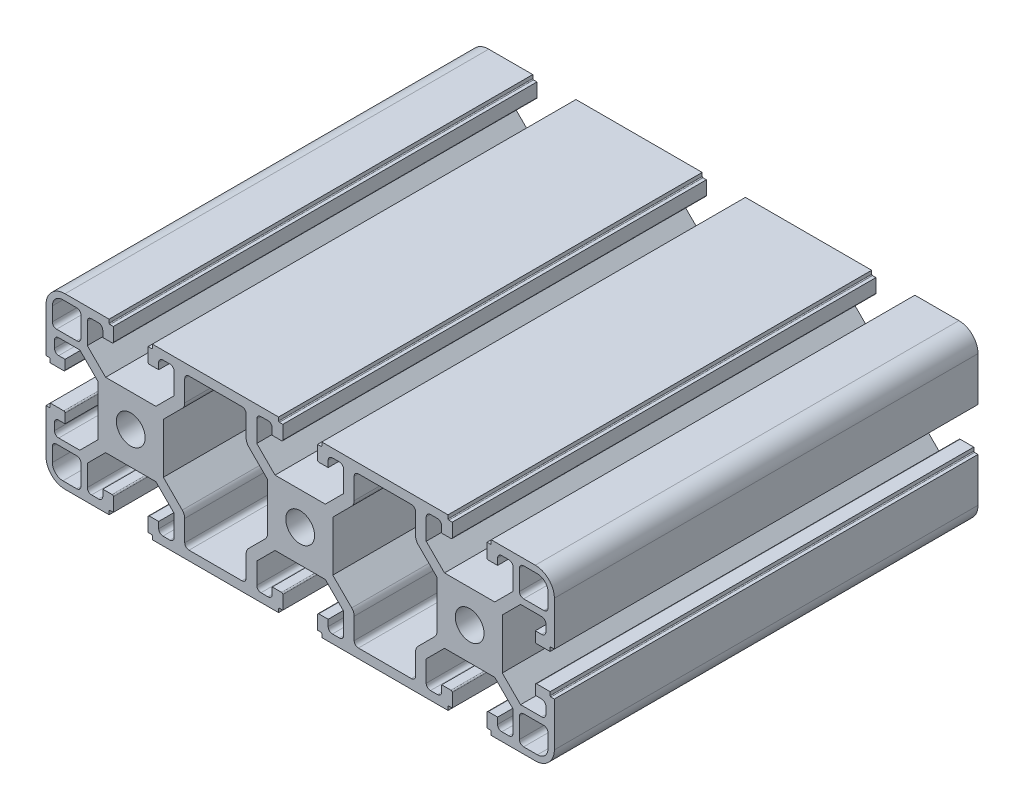
SolidWorks part; units mm, degrees
ref_plane "前视基准面" through (0, 0, 0) normal (0, 0, 1) x (1, 0, 0)
ref_plane "上视基准面" through (0, 0, 0) normal (0, 1, 0) x (1, 0, 0)
ref_plane "右视基准面" through (0, 0, 0) normal (1, 0, 0) x (0, 0, -1)
sketch "草图1" plane through (0, 0, 0) normal (0, 0, 1) x (1, 0, 0)
  line L0 (-45.8856, 20.757) -> (-56.2856, 20.757)
  line L1 (-60.7856, 16.257) -> (-60.7856, 5.857)
  line L2 (-47.3856, 16.257) -> (-47.3856, 17.757)
  line L3 (-48.3856, 18.757) -> (-50.0356, 18.757)
  line L4 (-51.0356, 17.757) -> (-51.0356, 12.7748)
  line L5 (-44.8856, 19.757) -> (-45.6856, 19.757)
  line L6 (-45.8856, 19.957) -> (-45.8856, 20.757)
  line L7 (-60.7856, 5.857) -> (-59.9856, 5.857)
  line L8 (-59.7856, 5.657) -> (-59.7856, 4.857)
  line L9 (-56.2856, 7.357) -> (-56.2856, 5.157)
  line L10 (-56.5856, 4.857) -> (-59.7856, 4.857)
  line L11 (-44.8856, 19.757) -> (-44.8856, 16.557)
  line L12 (-45.1856, 16.257) -> (-47.3856, 16.257)
  line L13 (-46.7178, 8.457) -> (-34.8534, 8.457)
  line L14 (-59.2896, 16.761) -> (-59.2896, 13.507)
  line L15 (-58.2896, 12.507) -> (-53.5356, 12.507)
  line L16 (-52.5356, 13.507) -> (-52.5356, 18.261)
  line L17 (-53.5356, 19.261) -> (-56.7896, 19.261)
  line L18 (-46.7178, -6.943) -> (-34.8534, -6.943)
  line L19 (-48.4856, 6.6892) -> (-48.4856, -5.1752)
  line L21 (-33.0856, -5.1752) -> (-33.0856, 6.6892)
  line L23 (-52.8034, 11.007) -> (-48.4856, 6.6892)
  line L24 (-51.0356, 12.7748) -> (-46.7178, 8.457)
  line L25 (-56.2856, 7.357) -> (-57.7856, 7.357)
  line L26 (-58.7856, 8.357) -> (-58.7856, 10.007)
  line L27 (-57.7856, 11.007) -> (-52.8034, 11.007)
  line L28 (-35.6856, 20.757) -> (-25.2856, 20.757)
  line L29 (-34.1856, 16.257) -> (-34.1856, 17.757)
  line L30 (-33.1856, 18.757) -> (-31.5356, 18.757)
  line L31 (-30.5356, 17.757) -> (-30.5356, 12.7748)
  line L32 (-28.0356, 17.557) -> (-28.0356, 12.5677)
  line L33 (-36.6856, 19.757) -> (-35.8856, 19.757)
  line L34 (-35.6856, 19.957) -> (-35.6856, 20.757)
  line L35 (-36.6856, 19.757) -> (-36.6856, 16.557)
  line L36 (-36.3856, 16.257) -> (-34.1856, 16.257)
  line L37 (-28.6214, 11.1535) -> (-33.0856, 6.6892)
  line L38 (-30.5356, 12.7748) -> (-34.8534, 8.457)
  line L39 (-45.8856, -19.243) -> (-56.2856, -19.243)
  line L40 (-60.7856, -14.743) -> (-60.7856, -4.343)
  line L41 (-47.3856, -14.743) -> (-47.3856, -16.243)
  line L42 (-48.3856, -17.243) -> (-50.0356, -17.243)
  line L43 (-51.0356, -16.243) -> (-51.0356, -11.2608)
  line L44 (-44.8856, -18.243) -> (-45.6856, -18.243)
  line L45 (-45.8856, -18.443) -> (-45.8856, -19.243)
  line L46 (-60.7856, -4.343) -> (-59.9856, -4.343)
  line L47 (-59.7856, -4.143) -> (-59.7856, -3.343)
  line L48 (-56.2856, -5.843) -> (-56.2856, -3.643)
  line L49 (-56.5856, -3.343) -> (-59.7856, -3.343)
  line L50 (-44.8856, -18.243) -> (-44.8856, -15.043)
  line L51 (-45.1856, -14.743) -> (-47.3856, -14.743)
  line L52 (-59.2896, -15.247) -> (-59.2896, -11.993)
  line L53 (-58.2896, -10.993) -> (-53.5356, -10.993)
  line L54 (-52.5356, -11.993) -> (-52.5356, -16.747)
  line L55 (-53.5356, -17.747) -> (-56.7896, -17.747)
  line L56 (-52.8034, -9.493) -> (-48.4856, -5.1752)
  line L57 (-51.0356, -11.2608) -> (-46.7178, -6.943)
  line L58 (-56.2856, -5.843) -> (-57.7856, -5.843)
  line L59 (-58.7856, -6.843) -> (-58.7856, -8.493)
  line L60 (-57.7856, -9.493) -> (-52.8034, -9.493)
  line L61 (-35.6856, -19.243) -> (-25.2856, -19.243)
  line L62 (-34.1856, -14.743) -> (-34.1856, -16.243)
  line L63 (-33.1856, -17.243) -> (-31.5356, -17.243)
  line L64 (-30.5356, -16.243) -> (-30.5356, -11.2608)
  line L65 (-36.6856, -18.243) -> (-35.8856, -18.243)
  line L66 (-35.6856, -18.443) -> (-35.6856, -19.243)
  line L67 (-36.6856, -18.243) -> (-36.6856, -15.043)
  line L68 (-36.3856, -14.743) -> (-34.1856, -14.743)
  line L69 (-28.6214, -9.6394) -> (-33.0856, -5.1752)
  line L70 (-30.5356, -11.2608) -> (-34.8534, -6.943)
  line L71 (-5.8856, 20.757) -> (-16.2856, 20.757)
  line L72 (-7.3856, 16.257) -> (-7.3856, 17.757)
  line L73 (-8.3856, 18.757) -> (-10.0356, 18.757)
  line L74 (-11.0356, 17.757) -> (-11.0356, 12.7748)
  line L75 (-13.5356, 17.557) -> (-13.5356, 12.5677)
  line L76 (-4.8856, 19.757) -> (-5.6856, 19.757)
  line L77 (-5.8856, 19.957) -> (-5.8856, 20.757)
  line L78 (-4.8856, 19.757) -> (-4.8856, 16.557)
  line L79 (-5.1856, 16.257) -> (-7.3856, 16.257)
  line L80 (-6.7178, 8.457) -> (5.1466, 8.457)
  line L81 (-6.7178, -6.943) -> (5.1466, -6.943)
  line L82 (-8.4856, 6.6892) -> (-8.4856, -4.3468)
  line L83 (-9.0714, -5.761) -> (-12.9498, -9.6394)
  line L85 (6.9144, -5.1752) -> (6.9144, 6.6892)
  line L87 (-12.9498, 11.1535) -> (-8.4856, 6.6892)
  line L88 (-11.0356, 12.7748) -> (-6.7178, 8.457)
  line L89 (5.8144, 16.257) -> (5.8144, 17.757)
  line L90 (6.8144, 18.757) -> (8.4644, 18.757)
  line L91 (9.4644, 17.757) -> (9.4644, 12.7748)
  line L92 (3.3144, 19.757) -> (4.1144, 19.757)
  line L93 (4.3144, 19.957) -> (4.3144, 20.757)
  line L94 (3.3144, 19.757) -> (3.3144, 16.557)
  line L95 (3.6144, 16.257) -> (5.8144, 16.257)
  line L97 (9.4644, 12.7748) -> (5.1466, 8.457)
  line L98 (-5.8856, -19.243) -> (-16.2856, -19.243)
  line L99 (-7.3856, -14.743) -> (-7.3856, -16.243)
  line L100 (-8.3856, -17.243) -> (-10.0356, -17.243)
  line L101 (-11.0356, -16.243) -> (-11.0356, -11.2608)
  line L102 (-4.8856, -18.243) -> (-5.6856, -18.243)
  line L103 (-5.8856, -18.443) -> (-5.8856, -19.243)
  line L104 (-4.8856, -18.243) -> (-4.8856, -15.043)
  line L105 (-5.1856, -14.743) -> (-7.3856, -14.743)
  line L106 (-11.0356, -11.2608) -> (-6.7178, -6.943)
  line L107 (5.8144, -14.743) -> (5.8144, -16.243)
  line L108 (6.8144, -17.243) -> (8.4644, -17.243)
  line L109 (9.4644, -16.243) -> (9.4644, -11.2608)
  line L110 (3.3144, -18.243) -> (4.1144, -18.243)
  line L111 (4.3144, -18.443) -> (4.3144, -19.243)
  line L112 (3.3144, -18.243) -> (3.3144, -15.043)
  line L113 (3.6144, -14.743) -> (5.8144, -14.743)
  line L115 (9.4644, -11.2608) -> (5.1466, -6.943)
  line L116 (-25.2856, -19.243) -> (-16.2856, -19.243)
  line L117 (-25.2856, 20.757) -> (-16.2856, 20.757)
  line L118 (-14.5356, 18.557) -> (-27.0356, 18.557)
  line L119 (-28.0356, -16.043) -> (-28.0356, -11.0536)
  line L120 (-13.5356, -16.043) -> (-13.5356, -11.0536)
  line L121 (-14.5356, -17.043) -> (-27.0356, -17.043)
  line L123 (11.9644, 17.557) -> (11.9644, 12.5677)
  line L124 (11.3786, 11.1535) -> (6.9144, 6.6892)
  line L125 (11.3786, -9.6394) -> (6.9144, -5.1752)
  line L126 (26.4644, 17.557) -> (26.4644, 12.5677)
  line L127 (31.5144, 6.6892) -> (31.5144, -4.3468)
  line L128 (30.9286, -5.761) -> (27.0502, -9.6394)
  line L129 (27.0502, 11.1535) -> (31.5144, 6.6892)
  line L130 (25.4644, 18.557) -> (12.9644, 18.557)
  line L131 (11.9644, -16.043) -> (11.9644, -11.0536)
  line L132 (26.4644, -16.043) -> (26.4644, -11.0536)
  line L133 (25.4644, -17.043) -> (12.9644, -17.043)
  line L134 (4.3144, -19.243) -> (34.1144, -19.243)
  line L135 (44.3144, 20.757) -> (54.7144, 20.757)
  line L136 (59.2144, 16.257) -> (59.2144, 5.857)
  line L137 (45.8144, 16.257) -> (45.8144, 17.757)
  line L138 (46.8144, 18.757) -> (48.4644, 18.757)
  line L139 (49.4644, 17.757) -> (49.4644, 12.7748)
  line L140 (43.3144, 19.757) -> (44.1144, 19.757)
  line L141 (44.3144, 19.957) -> (44.3144, 20.757)
  line L142 (43.3144, 19.757) -> (43.3144, 16.557)
  line L143 (43.6144, 16.257) -> (45.8144, 16.257)
  line L144 (57.7184, 16.761) -> (57.7184, 13.507)
  line L145 (56.7184, 12.507) -> (51.9644, 12.507)
  line L146 (50.9644, 13.507) -> (50.9644, 18.261)
  line L147 (51.9644, 19.261) -> (55.2184, 19.261)
  line L148 (46.9144, 6.6892) -> (46.9144, -5.1752)
  line L149 (45.1466, -6.943) -> (33.2822, -6.943)
  line L150 (33.2822, 8.457) -> (45.1466, 8.457)
  line L151 (51.2322, 11.007) -> (46.9144, 6.6892)
  line L152 (49.4644, 12.7748) -> (45.1466, 8.457)
  line L153 (54.7144, 7.357) -> (56.2144, 7.357)
  line L154 (57.2144, 8.357) -> (57.2144, 10.007)
  line L155 (56.2144, 11.007) -> (51.2322, 11.007)
  line L156 (44.3144, -19.243) -> (54.7144, -19.243)
  line L157 (59.2144, -14.743) -> (59.2144, -4.343)
  line L158 (45.8144, -14.743) -> (45.8144, -16.243)
  line L159 (46.8144, -17.243) -> (48.4644, -17.243)
  line L160 (49.4644, -16.243) -> (49.4644, -11.2608)
  line L161 (43.3144, -18.243) -> (44.1144, -18.243)
  line L162 (44.3144, -18.443) -> (44.3144, -19.243)
  line L163 (59.2144, -4.343) -> (58.4144, -4.343)
  line L164 (58.2144, -4.143) -> (58.2144, -3.343)
  line L165 (54.7144, -5.843) -> (54.7144, -3.643)
  line L166 (55.0144, -3.343) -> (58.2144, -3.343)
  line L167 (43.3144, -18.243) -> (43.3144, -15.043)
  line L168 (43.6144, -14.743) -> (45.8144, -14.743)
  line L169 (57.7184, -15.247) -> (57.7184, -11.993)
  line L170 (56.7184, -10.993) -> (51.9644, -10.993)
  line L171 (50.9644, -11.993) -> (50.9644, -16.747)
  line L172 (51.9644, -17.747) -> (55.2184, -17.747)
  line L173 (51.2322, -9.493) -> (46.9144, -5.1752)
  line L174 (49.4644, -11.2608) -> (45.1466, -6.943)
  line L175 (54.7144, -5.843) -> (56.2144, -5.843)
  line L176 (57.2144, -6.843) -> (57.2144, -8.493)
  line L177 (56.2144, -9.493) -> (51.2322, -9.493)
  line L178 (34.1144, 20.757) -> (4.3144, 20.757)
  line L179 (32.6144, 16.257) -> (32.6144, 17.757)
  line L180 (31.6144, 18.757) -> (29.9644, 18.757)
  line L181 (28.9644, 17.757) -> (28.9644, 12.7748)
  line L182 (35.1144, 19.757) -> (34.3144, 19.757)
  line L183 (34.1144, 19.957) -> (34.1144, 20.757)
  line L184 (35.1144, 19.757) -> (35.1144, 16.557)
  line L185 (34.8144, 16.257) -> (32.6144, 16.257)
  line L186 (28.9644, 12.7748) -> (33.2822, 8.457)
  line L188 (32.6144, -14.743) -> (32.6144, -16.243)
  line L189 (31.6144, -17.243) -> (29.9644, -17.243)
  line L190 (28.9644, -16.243) -> (28.9644, -11.2608)
  line L191 (35.1144, -18.243) -> (34.3144, -18.243)
  line L192 (34.1144, -18.443) -> (34.1144, -19.243)
  line L193 (35.1144, -18.243) -> (35.1144, -15.043)
  line L194 (34.8144, -14.743) -> (32.6144, -14.743)
  line L195 (28.9644, -11.2608) -> (33.2822, -6.943)
  line L196 (54.7144, 7.357) -> (54.7144, 5.157)
  line L197 (55.0144, 4.857) -> (58.2144, 4.857)
  line L198 (59.2144, 5.857) -> (58.4144, 5.857)
  line L199 (58.2144, 5.657) -> (58.2144, 4.857)
  arc A0 (-56.2856, 20.757) -> (-60.7856, 16.257) centre (-56.2856, 16.257) ccw
  arc A1 (-47.3856, 17.757) -> (-48.3856, 18.757) centre (-48.3856, 17.757) ccw
  arc A2 (-50.0356, 18.757) -> (-51.0356, 17.757) centre (-50.0356, 17.757) ccw
  arc A3 (-45.8856, 19.957) -> (-45.6856, 19.757) centre (-45.6856, 19.957) ccw
  arc A4 (-59.7856, 5.657) -> (-59.9856, 5.857) centre (-59.9856, 5.657) ccw
  arc A5 (-56.5856, 4.857) -> (-56.2856, 5.157) centre (-56.5856, 5.157) ccw
  arc A6 (-45.1856, 16.257) -> (-44.8856, 16.557) centre (-45.1856, 16.557) ccw
  circle A7 centre (-40.7856, 0.757) radius 3.4
  arc A8 (-59.2896, 13.507) -> (-58.2896, 12.507) centre (-58.2896, 13.507) ccw
  arc A9 (-52.5356, 18.261) -> (-53.5356, 19.261) centre (-53.5356, 18.261) ccw
  arc A10 (-53.5356, 12.507) -> (-52.5356, 13.507) centre (-53.5356, 13.507) ccw
  arc A11 (-56.7896, 19.261) -> (-59.2896, 16.761) centre (-56.7896, 16.761) ccw
  arc A12 (-58.7856, 8.357) -> (-57.7856, 7.357) centre (-57.7856, 8.357) ccw
  arc A13 (-57.7856, 11.007) -> (-58.7856, 10.007) centre (-57.7856, 10.007) ccw
  arc A14 (-33.1856, 18.757) -> (-34.1856, 17.757) centre (-33.1856, 17.757) ccw
  arc A15 (-30.5356, 17.757) -> (-31.5356, 18.757) centre (-31.5356, 17.757) ccw
  arc A16 (-35.8856, 19.757) -> (-35.6856, 19.957) centre (-35.8856, 19.957) ccw
  arc A17 (-36.6856, 16.557) -> (-36.3856, 16.257) centre (-36.3856, 16.557) ccw
  arc A18 (-28.6214, 11.1535) -> (-28.0356, 12.5677) centre (-30.0356, 12.5677) ccw
  arc A19 (-60.7856, -14.743) -> (-56.2856, -19.243) centre (-56.2856, -14.743) ccw
  arc A20 (-48.3856, -17.243) -> (-47.3856, -16.243) centre (-48.3856, -16.243) ccw
  arc A21 (-51.0356, -16.243) -> (-50.0356, -17.243) centre (-50.0356, -16.243) ccw
  arc A22 (-45.6856, -18.243) -> (-45.8856, -18.443) centre (-45.6856, -18.443) ccw
  arc A23 (-59.9856, -4.343) -> (-59.7856, -4.143) centre (-59.9856, -4.143) ccw
  arc A24 (-56.2856, -3.643) -> (-56.5856, -3.343) centre (-56.5856, -3.643) ccw
  arc A25 (-44.8856, -15.043) -> (-45.1856, -14.743) centre (-45.1856, -15.043) ccw
  arc A26 (-58.2896, -10.993) -> (-59.2896, -11.993) centre (-58.2896, -11.993) ccw
  arc A27 (-53.5356, -17.747) -> (-52.5356, -16.747) centre (-53.5356, -16.747) ccw
  arc A28 (-52.5356, -11.993) -> (-53.5356, -10.993) centre (-53.5356, -11.993) ccw
  arc A29 (-59.2896, -15.247) -> (-56.7896, -17.747) centre (-56.7896, -15.247) ccw
  arc A30 (-57.7856, -5.843) -> (-58.7856, -6.843) centre (-57.7856, -6.843) ccw
  arc A31 (-58.7856, -8.493) -> (-57.7856, -9.493) centre (-57.7856, -8.493) ccw
  arc A32 (-34.1856, -16.243) -> (-33.1856, -17.243) centre (-33.1856, -16.243) ccw
  arc A33 (-31.5356, -17.243) -> (-30.5356, -16.243) centre (-31.5356, -16.243) ccw
  arc A34 (-35.6856, -18.443) -> (-35.8856, -18.243) centre (-35.8856, -18.443) ccw
  arc A35 (-36.3856, -14.743) -> (-36.6856, -15.043) centre (-36.3856, -15.043) ccw
  arc A36 (-28.0356, -11.0536) -> (-28.6214, -9.6394) centre (-30.0356, -11.0536) ccw
  arc A37 (-7.3856, 17.757) -> (-8.3856, 18.757) centre (-8.3856, 17.757) ccw
  arc A38 (-13.5356, 17.557) -> (-14.5356, 18.557) centre (-14.5356, 17.557) ccw
  arc A39 (-10.0356, 18.757) -> (-11.0356, 17.757) centre (-10.0356, 17.757) ccw
  arc A40 (-5.8856, 19.957) -> (-5.6856, 19.757) centre (-5.6856, 19.957) ccw
  arc A41 (-5.1856, 16.257) -> (-4.8856, 16.557) centre (-5.1856, 16.557) ccw
  circle A42 centre (-0.7856, 0.757) radius 3.4
  arc A43 (-9.0714, -5.761) -> (-8.4856, -4.3468) centre (-10.4856, -4.3468) ccw
  arc A44 (-13.5356, 12.5677) -> (-12.9498, 11.1535) centre (-11.5356, 12.5677) ccw
  arc A45 (6.8144, 18.757) -> (5.8144, 17.757) centre (6.8144, 17.757) ccw
  arc A46 (9.4644, 17.757) -> (8.4644, 18.757) centre (8.4644, 17.757) ccw
  arc A47 (4.1144, 19.757) -> (4.3144, 19.957) centre (4.1144, 19.957) ccw
  arc A48 (3.3144, 16.557) -> (3.6144, 16.257) centre (3.6144, 16.557) ccw
  arc A49 (-8.3856, -17.243) -> (-7.3856, -16.243) centre (-8.3856, -16.243) ccw
  arc A50 (-11.0356, -16.243) -> (-10.0356, -17.243) centre (-10.0356, -16.243) ccw
  arc A51 (-5.6856, -18.243) -> (-5.8856, -18.443) centre (-5.6856, -18.443) ccw
  arc A52 (-4.8856, -15.043) -> (-5.1856, -14.743) centre (-5.1856, -15.043) ccw
  arc A53 (-12.9498, -9.6394) -> (-13.5356, -11.0536) centre (-11.5356, -11.0536) ccw
  arc A54 (5.8144, -16.243) -> (6.8144, -17.243) centre (6.8144, -16.243) ccw
  arc A55 (8.4644, -17.243) -> (9.4644, -16.243) centre (8.4644, -16.243) ccw
  arc A56 (4.3144, -18.443) -> (4.1144, -18.243) centre (4.1144, -18.443) ccw
  arc A57 (3.6144, -14.743) -> (3.3144, -15.043) centre (3.6144, -15.043) ccw
  arc A58 (-27.0356, 18.557) -> (-28.0356, 17.557) centre (-27.0356, 17.557) ccw
  arc A59 (-28.0356, -16.043) -> (-27.0356, -17.043) centre (-27.0356, -16.043) ccw
  arc A60 (-14.5356, -17.043) -> (-13.5356, -16.043) centre (-14.5356, -16.043) ccw
  arc A61 (11.3786, 11.1535) -> (11.9644, 12.5677) centre (9.9644, 12.5677) ccw
  arc A62 (11.9644, -11.0536) -> (11.3786, -9.6394) centre (9.9644, -11.0536) ccw
  arc A63 (26.4644, 17.557) -> (25.4644, 18.557) centre (25.4644, 17.557) ccw
  arc A64 (30.9286, -5.761) -> (31.5144, -4.3468) centre (29.5144, -4.3468) ccw
  arc A65 (26.4644, 12.5677) -> (27.0502, 11.1535) centre (28.4644, 12.5677) ccw
  arc A66 (27.0502, -9.6394) -> (26.4644, -11.0536) centre (28.4644, -11.0536) ccw
  arc A67 (12.9644, 18.557) -> (11.9644, 17.557) centre (12.9644, 17.557) ccw
  arc A68 (11.9644, -16.043) -> (12.9644, -17.043) centre (12.9644, -16.043) ccw
  arc A69 (25.4644, -17.043) -> (26.4644, -16.043) centre (25.4644, -16.043) ccw
  arc A70 (59.2144, 16.257) -> (54.7144, 20.757) centre (54.7144, 16.257) ccw
  arc A71 (46.8144, 18.757) -> (45.8144, 17.757) centre (46.8144, 17.757) ccw
  arc A72 (49.4644, 17.757) -> (48.4644, 18.757) centre (48.4644, 17.757) ccw
  arc A73 (44.1144, 19.757) -> (44.3144, 19.957) centre (44.1144, 19.957) ccw
  arc A74 (43.3144, 16.557) -> (43.6144, 16.257) centre (43.6144, 16.557) ccw
  circle A75 centre (39.2144, 0.757) radius 3.4
  arc A76 (51.9644, 19.261) -> (50.9644, 18.261) centre (51.9644, 18.261) ccw
  arc A77 (50.9644, 13.507) -> (51.9644, 12.507) centre (51.9644, 13.507) ccw
  arc A78 (57.7184, 16.761) -> (55.2184, 19.261) centre (55.2184, 16.761) ccw
  arc A79 (56.2144, 7.357) -> (57.2144, 8.357) centre (56.2144, 8.357) ccw
  arc A80 (57.2144, 10.007) -> (56.2144, 11.007) centre (56.2144, 10.007) ccw
  arc A81 (54.7144, -19.243) -> (59.2144, -14.743) centre (54.7144, -14.743) ccw
  arc A82 (45.8144, -16.243) -> (46.8144, -17.243) centre (46.8144, -16.243) ccw
  arc A83 (48.4644, -17.243) -> (49.4644, -16.243) centre (48.4644, -16.243) ccw
  arc A84 (44.3144, -18.443) -> (44.1144, -18.243) centre (44.1144, -18.443) ccw
  arc A85 (58.2144, -4.143) -> (58.4144, -4.343) centre (58.4144, -4.143) ccw
  arc A86 (55.0144, -3.343) -> (54.7144, -3.643) centre (55.0144, -3.643) ccw
  arc A87 (43.6144, -14.743) -> (43.3144, -15.043) centre (43.6144, -15.043) ccw
  arc A88 (57.7184, -11.993) -> (56.7184, -10.993) centre (56.7184, -11.993) ccw
  arc A89 (50.9644, -16.747) -> (51.9644, -17.747) centre (51.9644, -16.747) ccw
  arc A90 (51.9644, -10.993) -> (50.9644, -11.993) centre (51.9644, -11.993) ccw
  arc A91 (55.2184, -17.747) -> (57.7184, -15.247) centre (55.2184, -15.247) ccw
  arc A92 (57.2144, -6.843) -> (56.2144, -5.843) centre (56.2144, -6.843) ccw
  arc A93 (56.2144, -9.493) -> (57.2144, -8.493) centre (56.2144, -8.493) ccw
  arc A94 (32.6144, 17.757) -> (31.6144, 18.757) centre (31.6144, 17.757) ccw
  arc A95 (29.9644, 18.757) -> (28.9644, 17.757) centre (29.9644, 17.757) ccw
  arc A96 (34.1144, 19.957) -> (34.3144, 19.757) centre (34.3144, 19.957) ccw
  arc A97 (34.8144, 16.257) -> (35.1144, 16.557) centre (34.8144, 16.557) ccw
  arc A98 (31.6144, -17.243) -> (32.6144, -16.243) centre (31.6144, -16.243) ccw
  arc A99 (28.9644, -16.243) -> (29.9644, -17.243) centre (29.9644, -16.243) ccw
  arc A100 (34.3144, -18.243) -> (34.1144, -18.443) centre (34.3144, -18.443) ccw
  arc A101 (35.1144, -15.043) -> (34.8144, -14.743) centre (34.8144, -15.043) ccw
  arc A102 (54.7144, 5.157) -> (55.0144, 4.857) centre (55.0144, 5.157) ccw
  arc A103 (58.4144, 5.857) -> (58.2144, 5.657) centre (58.4144, 5.657) ccw
  arc A104 (56.7184, 12.507) -> (57.7184, 13.507) centre (56.7184, 13.507) ccw
extrude "凸台-拉伸1" add sketch "草图1" along normal blind 100
